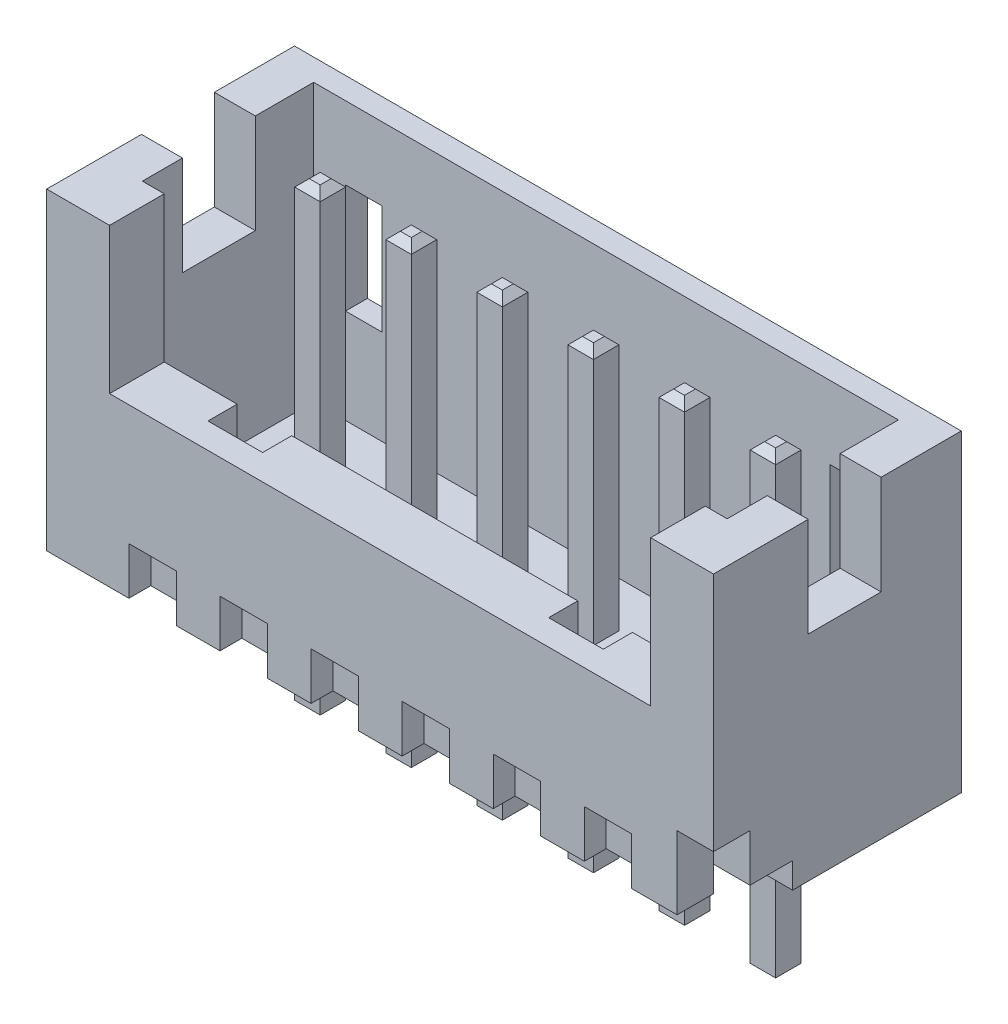
SolidWorks part; units mm, degrees
ref_plane "Спереди" through (0, 0, 0) normal (0, 0, 1) x (1, 0, 0)
ref_plane "Сверху" through (0, 0, 0) normal (0, 1, 0) x (1, 0, 0)
ref_plane "Справа" through (0, 0, 0) normal (1, 0, 0) x (0, 0, -1)
sketch "Эскиз1" plane through (0, 0, 0) normal (0, 1, 0) x (1, 0, 0)
  line L1 (-4.575, -1.7) -> (4.575, -1.7)
  line L2 (-4.575, -1.7) -> (-4.575, 1.7)
  line L3 (-4.575, 1.7) -> (4.575, 1.7)
  line L4 (4.575, -1.7) -> (4.575, 1.7)
  line L5 (-4.575, -1.7) -> (4.575, 1.7) construction
  line L6 (-4.575, 1.7) -> (4.575, -1.7) construction
  point P0 (0, 0)
  dimension "D1" = 3.4
  dimension "D2" = 9.15
extrude "Бобышка-Вытянуть1" add sketch "Эскиз1" along normal blind 4.3
sketch "Эскиз2" plane through (0, 4.3, 0) normal (0, 1, 0) x (1, 0, 0)
  line L0 (4.575, 1.7) -> (-4.575, 1.7) construction
  line L1 (-4.0125, -0.95) -> (4.0125, -0.95)
  line L2 (-4.0125, -0.95) -> (-4.0125, 1.4)
  line L3 (-4.0125, 1.4) -> (4.0125, 1.4)
  line L4 (4.0125, -0.95) -> (4.0125, 1.4)
  line L5 (-4.0125, -0.95) -> (4.0125, 1.4) construction
  line L6 (-4.0125, 1.4) -> (4.0125, -0.95) construction
  line L7 (0, -0.95) -> (0, 0) construction
  point P0 (0, 0)
  dimension "D1" = 2.35
  dimension "D2" = 8.025
  dimension "D3" = 0.3
extrude "Вырез-Вытянуть1" cut sketch "Эскиз2" against normal blind 3.8
sketch "Эскиз3" plane through (0, 0, 1.7) normal (0, 0, 1) x (1, 0, 0)
  line L0 (-4.575, 4.3) -> (4.575, 4.3) construction
  line L1 (-3.7125, 4.3) -> (3.7125, 4.3)
  line L2 (-3.7125, 4.3) -> (-3.7125, 2.3)
  line L3 (-3.7125, 2.3) -> (3.7125, 2.3)
  line L4 (3.7125, 4.3) -> (3.7125, 2.3)
  dimension "D1" = 0.3
  dimension "D2" = 0.3
  dimension "D3" = 2
extrude "Вырез-Вытянуть2" cut sketch "Эскиз3" against normal up to next
sketch "Эскиз4" plane through (0, 0, -1.7) normal (0, 0, -1) x (-1, 0, 0)
  line L0 (0, 0) -> (0, 4.3) construction
  line L1 (-3.575, 3.3) -> (-3.075, 3.3)
  line L2 (-3.575, 3.3) -> (-3.575, 1.8)
  line L3 (-3.575, 1.8) -> (-3.075, 1.8)
  line L4 (-3.075, 3.3) -> (-3.075, 1.8)
  line L5 (-4.575, 4.3) -> (4.575, 4.3) construction
  line L6 (-4.575, 4.3) -> (-4.575, 0) construction
  line L7 (3.075, 3.3) -> (3.075, 1.8)
  line L8 (3.575, 1.8) -> (3.075, 1.8)
  line L9 (3.575, 3.3) -> (3.575, 1.8)
  line L10 (3.575, 3.3) -> (3.075, 3.3)
  dimension "D1" = 0.5
  dimension "D2" = 1.5
  dimension "D3" = 1
  dimension "D4" = 1
extrude "Вырез-Вытянуть3" cut sketch "Эскиз4" against normal up to next
sketch "Эскиз5" plane through (0, 0.5, 0) normal (0, 1, 0) x (1, 0, 0)
  line L1 (-3.2975, 0.775) -> (-2.9475, 0.775)
  line L2 (-3.2975, 0.775) -> (-3.2975, 0.425)
  line L3 (-3.2975, 0.425) -> (-2.9475, 0.425)
  line L4 (-2.9475, 0.775) -> (-2.9475, 0.425)
  line L5 (-4.0125, 1.4) -> (-4.0125, -0.95) construction
  line L6 (4.0125, 1.4) -> (-4.0125, 1.4) construction
  point P4 (-2.9475, 0.6)
  dimension "D1" = 0.715
  dimension "D2" = 0.35
  dimension "D3" = 0.8
extrude "Pin" add sketch "Эскиз5" along normal blind 3.5 and the other way blind 2.8 separate body
chamfer "Фаска1" distance 0.1 angle 45 8 edges at (-2.9475, -2.3, -0.6) (-3.1225, -2.3, -0.775) (-3.2975, -2.3, -0.6) (-3.1225, -2.3, -0.425) (-2.9475, 4, -0.6) (-3.1225, 4, -0.775) (-3.2975, 4, -0.6) (-3.1225, 4, -0.425)
pattern_linear "Линейный массив3" count 6 spacing 1.25 along (1, 0, 0) of bodies 107
sketch "Эскиз6" plane through (-4.575, 0, 0) normal (-1, 0, 0) x (0, 0, 1)
  line L0 (-1.7, 4.3) -> (1.7, 4.3) construction
  line L1 (-0.6, 4.3) -> (0.4, 4.3)
  line L2 (-0.6, 4.3) -> (-0.6, 2.9368)
  line L3 (-0.6, 2.9368) -> (0.4, 2.9368)
  line L4 (0.4, 4.3) -> (0.4, 2.9368)
  dimension "D1" = 1
  dimension "D2" = 0.8
extrude "Вырез-Вытянуть5" cut sketch "Эскиз6" against normal up to next (0.5625 mm away)
sketch "Эскиз7" plane through (0, 2.3, 0) normal (0, 1, 0) x (1, 0, 0)
  line L0 (3.7125, -0.95) -> (-3.7125, -0.95) construction
  line L1 (-2.7125, -0.95) -> (-1.9625, -0.95)
  line L2 (-2.7125, -0.95) -> (-2.7125, -1.35)
  line L3 (-2.7125, -1.35) -> (-1.9625, -1.35)
  line L4 (-1.9625, -0.95) -> (-1.9625, -1.35)
  line L5 (-3.7125, -0.95) -> (-3.7125, -1.7) construction
  dimension "D1" = 0.75
  dimension "D2" = 1
  dimension "D3" = 0.4
extrude "Вырез-Вытянуть6" cut sketch "Эскиз7" against normal up to surface (1.8 mm away) up to face at (0, 0.5, -0.225)
mirror "Зеркальное отражение1" about plane through (0, 0, 0) normal (1, 0, 0) of "Вырез-Вытянуть6", "Вырез-Вытянуть5"
sketch "Эскиз8" plane through (0, 0, 1.7) normal (0, 0, 1) x (1, 0, 0)
  line L1 (4.575, 0) -> (4.075, 0)
  line L2 (4.575, 0) -> (4.575, 1)
  line L3 (4.575, 1) -> (4.075, 1)
  line L4 (4.075, 0) -> (4.075, 1)
  dimension "D1" = 0.5
  dimension "D2" = 1
extrude "Вырез-Вытянуть7" cut sketch "Эскиз8" against normal blind 0.5
sketch "Эскиз9" plane through (0, 0, 1.7) normal (0, 0, 1) x (1, 0, 0)
  line L0 (-4.575, 0) -> (4.075, 0) construction
  line L1 (-3.4475, 0) -> (-2.7975, 0)
  line L2 (-3.4475, 0) -> (-3.4475, 0.65)
  line L3 (-3.4475, 0.65) -> (-2.7975, 0.65)
  line L4 (-2.7975, 0) -> (-2.7975, 0.65)
  line L5 (-2.9475, 2.4661) -> (-3.2975, 2.4661) construction
  line L6 (-2.9475, -2.2) -> (-2.9475, 3.9) construction
  line L7 (-3.2975, -2.2) -> (-3.2975, 3.9) construction
  line L8 (-3.1225, 0.65) -> (-3.1225, 2.4661)
  point P12 (-3.1225, 2.4661)
  line M5 (-4.575, 0) -> (4.075, 0)
  dimension "D1" = 0.65
extrude "Вырез-Вытянуть8" cut sketch "Эскиз9" against normal blind 0.3 contours L4 L3 L2 M5
pattern_linear "Линейный массив4" count 6 spacing 1.25 along (1, 0, 0) of "Вырез-Вытянуть8"
sketch "Эскиз10" plane through (-4.575, 0, 0) normal (-1, 0, 0) x (0, 0, 1)
  line L0 (-1.7, 0) -> (1.7, 0) construction
  line L1 (1.2002, 0) -> (0.6147, 0)
  line L2 (1.2002, 0) -> (1.2002, 0.3511)
  line L3 (1.2002, 0.3511) -> (0.6147, 0.3511)
  line L4 (0.6147, 0) -> (0.6147, 0.3511)
extrude "Вырез-Вытянуть9" cut sketch "Эскиз10" against normal through all
equation "\"N\" = 6"
equation "\"D2@Эскиз1\"=\"N\"*1.25+1.65"
equation "\"D2@Эскиз2\"=\"N\"*1.25+0.525"
equation "\"D1@Линейный массив3\"=\"N\""
equation "\"D1@Линейный массив4\"=\"N\""
